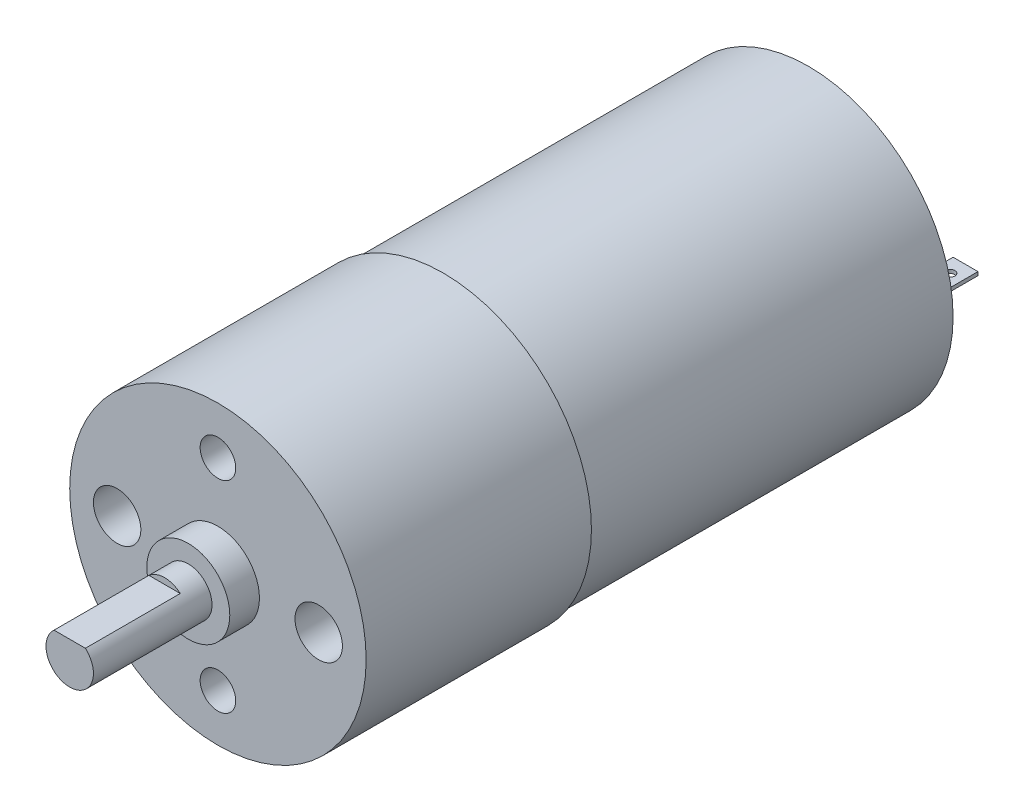
SolidWorks part; units mm, degrees
ref_plane "Front Plane" through (0, 0, 0) normal (0, 0, 1) x (1, 0, 0)
ref_plane "Top Plane" through (0, 0, 0) normal (0, 1, 0) x (1, 0, 0)
ref_plane "Right Plane" through (0, 0, 0) normal (1, 0, 0) x (0, 0, -1)
sketch "Sketch1" plane through (0, 0, 0) normal (0, 0, 1) x (1, 0, 0)
  line L0 (0, 0) -> (0, 8.5) construction
  line L1 (0, 0) -> (12.5, 0) construction
  circle A0 centre (0, 0) radius 12.5
  circle A1 centre (0, 0) radius 3.2
  circle A2 centre (0, 8.5) radius 1.5
  circle A3 centre (0, -8.5) radius 1.5
  dimension "D1" = 25
  dimension "D2" = 6.4
  dimension "D3" = 3
  dimension "D4" = 8.5
extrude "Boss-Extrude1" add sketch "Sketch1" along normal blind 19
sketch "Sketch3" plane through (0, 0, 0) normal (0, 0, -1) x (-1, 0, 0)
  circle A0 centre (0, 0) radius 3.2
  circle A1 centre (0, 0) radius 12.2
  dimension "D1" = 24.4
  dimension "D2" = 6.4
extrude "Boss-Extrude2" add sketch "Sketch3" along normal blind 30.8
sketch "Sketch4" plane through (0, 0, -30.8) normal (0, 0, -1) x (-1, 0, 0)
  line L0 (0, 12.2) -> (0, -12.2) construction
  line L1 (-12.2, 0) -> (12.2, 0) construction
  line L2 (10.1, 0.15) -> (8, 0.15)
  line L3 (-10.1, -0.15) -> (-8, -0.15)
  line L4 (-10.1, -0.15) -> (-10.1, 0.15)
  line L5 (-10.1, 0.15) -> (-8, 0.15)
  line L6 (-8, -0.15) -> (-8, 0.15)
  line L7 (-10.1, -0.15) -> (-8, 0.15) construction
  line L8 (-10.1, 0.15) -> (-8, -0.15) construction
  line L9 (8, -0.15) -> (8, 0.15)
  line L10 (10.1, -0.15) -> (8, -0.15)
  line L11 (10.1, -0.15) -> (10.1, 0.15)
  circle A0 centre (0, 0) radius 12.2 construction
  circle A1 centre (0, 0) radius 12.2 construction
  point P9 (-9.05, 0)
  point P18 (9.05, 0.15)
  dimension "D1" = 2.1
  dimension "D2" = 0.3
  dimension "D3" = 18.1
extrude "Boss-Extrude3" add sketch "Sketch4" along normal blind 4.2
sketch "Sketch6" plane through (0, 0, 19) normal (0, 0, 1) x (1, 0, 0)
  circle A0 centre (0, 0) radius 3.5
  circle A1 centre (0, 0) radius 2
  dimension "D1" = 7
  dimension "D2" = 4
extrude "Boss-Extrude4" add sketch "Sketch6" along normal blind 2.5
sketch "Sketch7" plane through (0, 0, 19) normal (0, 0, 1) x (1, 0, 0)
  circle A0 centre (0, 0) radius 2
  dimension "D1" = 4
extrude "Boss-Extrude5" add sketch "Sketch7" along normal blind 12.5
sketch "Sketch9" plane through (0, 0, 31.5) normal (0, 0, 1) x (1, 0, 0)
  line L0 (-1.3229, 1.5) -> (1.3229, 1.5)
  circle A0 centre (0, -0.25) radius 1.75 construction
  circle A1 centre (0, 0) radius 2
  point P7 (0, 1.5)
  circle M2 centre (0, 0) radius 2
  dimension "D1" = 3.5
  dimension "D2" = 4
extrude "Cut-Extrude1" cut sketch "Sketch9" against normal blind 8 contours L0 M2
sketch "Sketch10" plane through (0, 0, 19) normal (0, 0, 1) x (1, 0, 0)
  line L0 (-12.5, 0) -> (12.5, 0) construction
  line L1 (0, -12.5) -> (0, 12.5) construction
  circle A0 centre (0, 0) radius 12.5 construction
  circle A1 centre (-8.5, 0) radius 2
  circle A2 centre (8.5, 0) radius 2
  dimension "D1" = 4
  dimension "D2" = 8.5
extrude "Cut-Extrude2" cut sketch "Sketch10" against normal blind 6
sketch "Sketch11" plane through (0, 0, -30.8) normal (0, 0, -1) x (-1, 0, 0)
  circle A0 centre (0, 0) radius 3.2
  dimension "D1" = 6.4
extrude "Boss-Extrude6" add sketch "Sketch11" along normal blind 1 separate body
sketch "Sketch12" plane through (0, 0, -31.8) normal (0, 0, -1) x (-1, 0, 0)
  circle A0 centre (0, 0) radius 3.2
  dimension "D1" = 6.4
extrude "Boss-Extrude7" add sketch "Sketch12" along normal blind 0.5 draft 23
sketch "Sketch13" plane through (0, 0.15, 0) normal (0, 1, 0) x (1, 0, 0)
  line L1 (8, 35) -> (10.1, 35) construction
  circle A0 centre (9.05, 33.7) radius 0.4
  point P6 (9.05, 35)
  dimension "D1" = 0.8
  dimension "D2" = 1.3
extrude "Cut-Extrude3" cut sketch "Sketch13" against normal blind 0.5
sketch "Sketch14" plane through (0, 0.15, 0) normal (0, 1, 0) x (1, 0, 0)
  line L0 (-10.1, 35) -> (-8, 35) construction
  circle A0 centre (-9.05, 33.7) radius 0.4
  point P5 (-9.05, 35)
  dimension "D1" = 0.8
  dimension "D2" = 1.3
extrude "Cut-Extrude4" cut sketch "Sketch14" against normal blind 0.5
